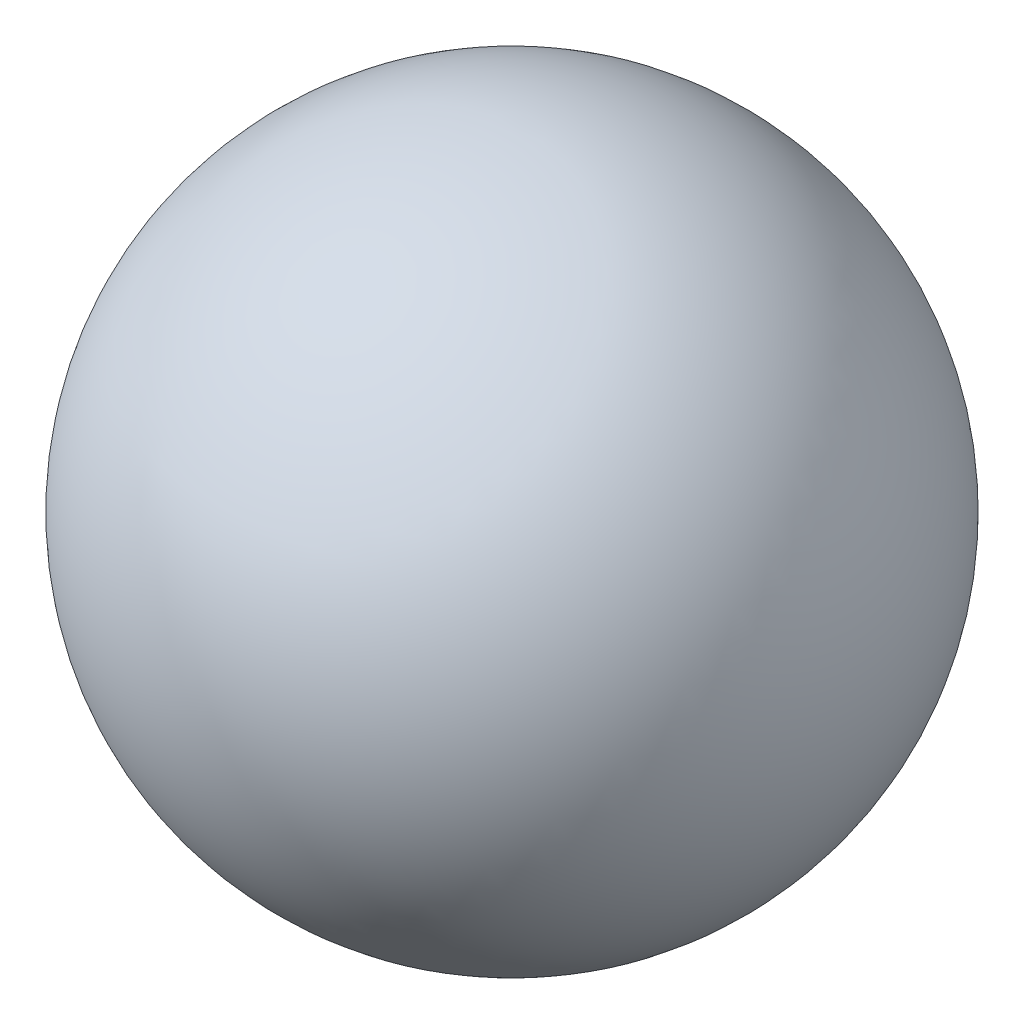
SolidWorks part; units mm, degrees
ref_plane "Front Plane" through (0, 0, 0) normal (0, 0, 1) x (1, 0, 0)
ref_plane "Top Plane" through (0, 0, 0) normal (0, 1, 0) x (1, 0, 0)
ref_plane "Right Plane" through (0, 0, 0) normal (1, 0, 0) x (0, 0, -1)
sketch "Sketch1" plane through (0, 0, 0) normal (0, 0, 1) x (1, 0, 0)
  line L0 (0, -3.21) -> (0, -4.7275)
  line L1 (0, -3.21) -> (0, -4.7275) construction
  arc A0 (0, -4.7275) -> (0, -3.21) centre (0, -3.9688) ccw
revolve "Revolve1" add sketch "Sketch1" angle 360 about L1
